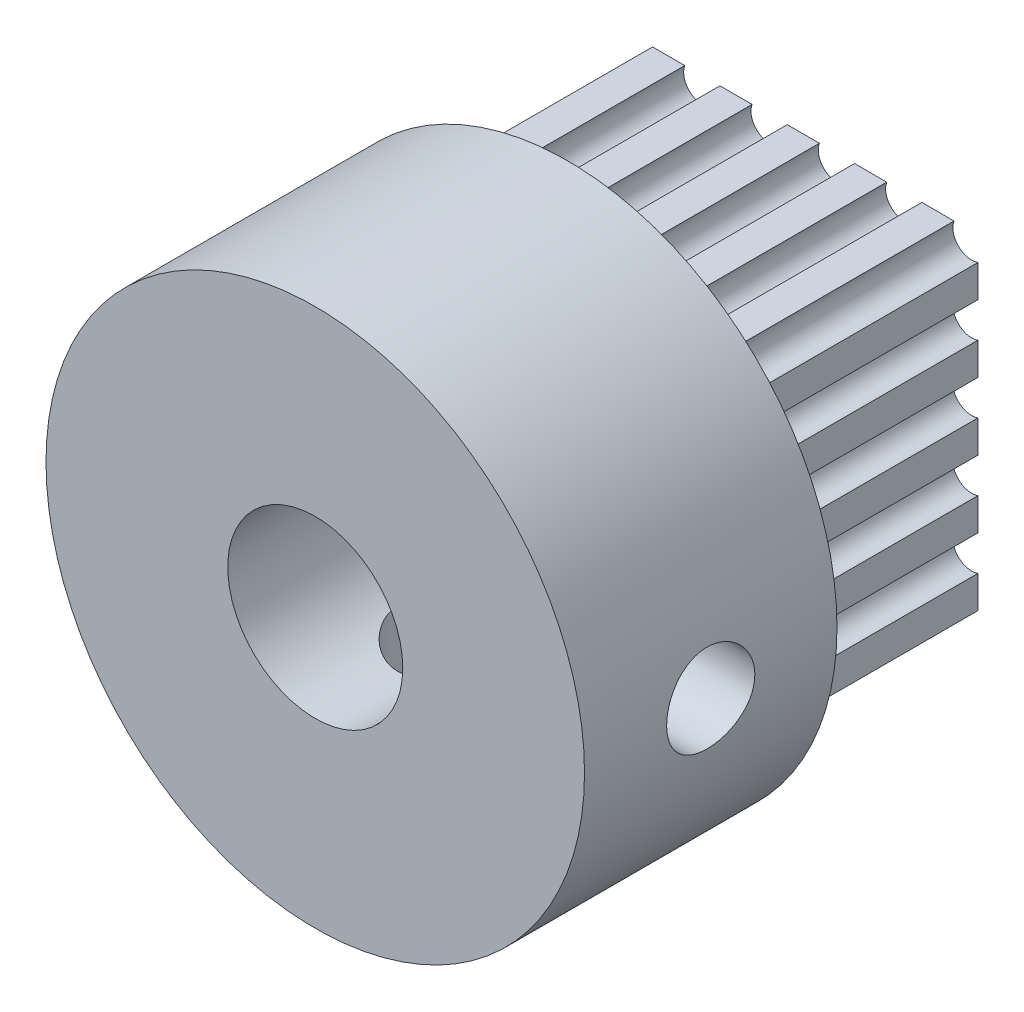
SolidWorks part; units mm, degrees
ref_plane "Front Plane" through (0, 0, 0) normal (0, 0, 1) x (1, 0, 0)
ref_plane "Top Plane" through (0, 0, 0) normal (0, 1, 0) x (1, 0, 0)
ref_plane "Right Plane" through (0, 0, 0) normal (1, 0, 0) x (0, 0, -1)
sketch "Sketch2" plane through (0, 0, 0) normal (0, 0, 1) x (1, 0, 0)
  line L0 (-8.1984, 4.754) -> (1.8016, -5.246) construction
  line L1 (-7.6769, 4.944) -> (-6.7198, 4.944)
  line L2 (-8.3884, 4.2325) -> (-8.3884, 3.2754)
  line L3 (-7.6769, -5.436) -> (-6.7198, -5.436)
  line L4 (1.9916, 4.2325) -> (1.9916, 3.2754)
  line L9 (-7.8059, -4.8536) -> (1.8016, 4.754) construction
  line L10 (-5.6769, 4.944) -> (-4.7198, 4.944)
  line L11 (-3.6769, 4.944) -> (-2.7198, 4.944)
  line L12 (-1.6769, 4.944) -> (-0.7198, 4.944)
  line L13 (0.3231, 4.944) -> (1.2802, 4.944)
  line L14 (1.9916, 2.2325) -> (1.9916, 1.2754)
  line L15 (1.9916, 0.2325) -> (1.9916, -0.7246)
  line L16 (1.9916, -1.7675) -> (1.9916, -2.7246)
  line L17 (1.9916, -3.7675) -> (1.9916, -4.7246)
  line L18 (0.3231, -5.436) -> (1.2802, -5.436)
  line L19 (-1.6769, -5.436) -> (-0.7198, -5.436)
  line L20 (-3.6769, -5.436) -> (-2.7198, -5.436)
  line L21 (-5.6769, -5.436) -> (-4.7198, -5.436)
  line L22 (-8.3884, -3.7675) -> (-8.3884, -4.7246)
  line L23 (-8.3884, -1.7675) -> (-8.3884, -2.7246)
  line L24 (-8.3884, 0.2325) -> (-8.3884, -0.7246)
  line L25 (-8.3884, 2.2325) -> (-8.3884, 1.2754)
  arc A0 (-8.3884, 4.2325) -> (-7.6769, 4.944) centre (-8.1984, 4.754) ccw
  arc A1 (-6.7198, 4.944) -> (-5.6769, 4.944) centre (-6.1984, 4.754) ccw
  arc A2 (-4.7198, 4.944) -> (-3.6769, 4.944) centre (-4.1984, 4.754) ccw
  arc A3 (-2.7198, 4.944) -> (-1.6769, 4.944) centre (-2.1984, 4.754) ccw
  arc A4 (-0.7198, 4.944) -> (0.3231, 4.944) centre (-0.1984, 4.754) ccw
  arc A5 (1.2802, 4.944) -> (1.9916, 4.2325) centre (1.8016, 4.754) ccw
  arc A6 (1.9916, 3.2754) -> (1.9916, 2.2325) centre (1.8016, 2.754) ccw
  arc A7 (1.9916, 1.2754) -> (1.9916, 0.2325) centre (1.8016, 0.754) ccw
  arc A8 (1.9916, -0.7246) -> (1.9916, -1.7675) centre (1.8016, -1.246) ccw
  arc A9 (1.9916, -2.7246) -> (1.9916, -3.7675) centre (1.8016, -3.246) ccw
  arc A10 (1.9916, -4.7246) -> (1.2802, -5.436) centre (1.8016, -5.246) ccw
  arc A11 (0.3231, -5.436) -> (-0.7198, -5.436) centre (-0.1984, -5.246) ccw
  arc A12 (-1.6769, -5.436) -> (-2.7198, -5.436) centre (-2.1984, -5.246) ccw
  arc A13 (-3.6769, -5.436) -> (-4.7198, -5.436) centre (-4.1984, -5.246) ccw
  arc A14 (-5.6769, -5.436) -> (-6.7198, -5.436) centre (-6.1984, -5.246) ccw
  arc A15 (-7.6769, -5.436) -> (-8.3884, -4.7246) centre (-8.1984, -5.246) ccw
  arc A16 (-8.3884, -3.7675) -> (-8.3884, -2.7246) centre (-8.1984, -3.246) ccw
  arc A17 (-8.3884, -1.7675) -> (-8.3884, -0.7246) centre (-8.1984, -1.246) ccw
  arc A18 (-8.3884, 0.2325) -> (-8.3884, 1.2754) centre (-8.1984, 0.754) ccw
  arc A19 (-8.3884, 2.2325) -> (-8.3884, 3.2754) centre (-8.1984, 2.754) ccw
  circle A20 centre (-3.1984, -0.246) radius 4.1
  circle A21 centre (-3.1984, -0.246) radius 2.6
  dimension "D7" = 6
  dimension "D8" = 6
  dimension "D9" = 6
  dimension "D10" = 5
extrude "Boss-Extrude1" add sketch "Sketch2" along normal blind 7 contours A20 A21 | A19 L25 A18 L24 A17 L23 A16 L22 A15 L3 A14 L21 A13 L20 A12 L19 A11 L18 A10 L17 A9 L16 A8 L15 A7 L14 A6 L4 A5 L13 A4 L12 A3 L11 A2 L10 A1 L1 A0 L2 A20
sketch "Sketch3" plane through (0, 0, 7) normal (0, 0, 1) x (1, 0, 0)
  circle A0 centre (-3.1984, -0.246) radius 8
  circle A1 centre (-3.1984, -0.246) radius 2.6
extrude "Boss-Extrude2" add sketch "Sketch3" along normal blind 7.5
sketch "Sketch4" plane through (0, 0, 0) normal (0, 1, 0) x (1, 0, 0)
  circle A0 centre (-3.1984, -10.75) radius 1.31
extrude "Cut-Extrude1" cut sketch "Sketch4" against normal blind 9
sketch "Sketch5" plane through (0, 0, 0) normal (1, 0, 0) x (0, 0, -1)
  circle A0 centre (-10.75, -0.246) radius 1.31
extrude "Cut-Extrude2" cut sketch "Sketch5" along normal blind 5 and the other way blind 2
